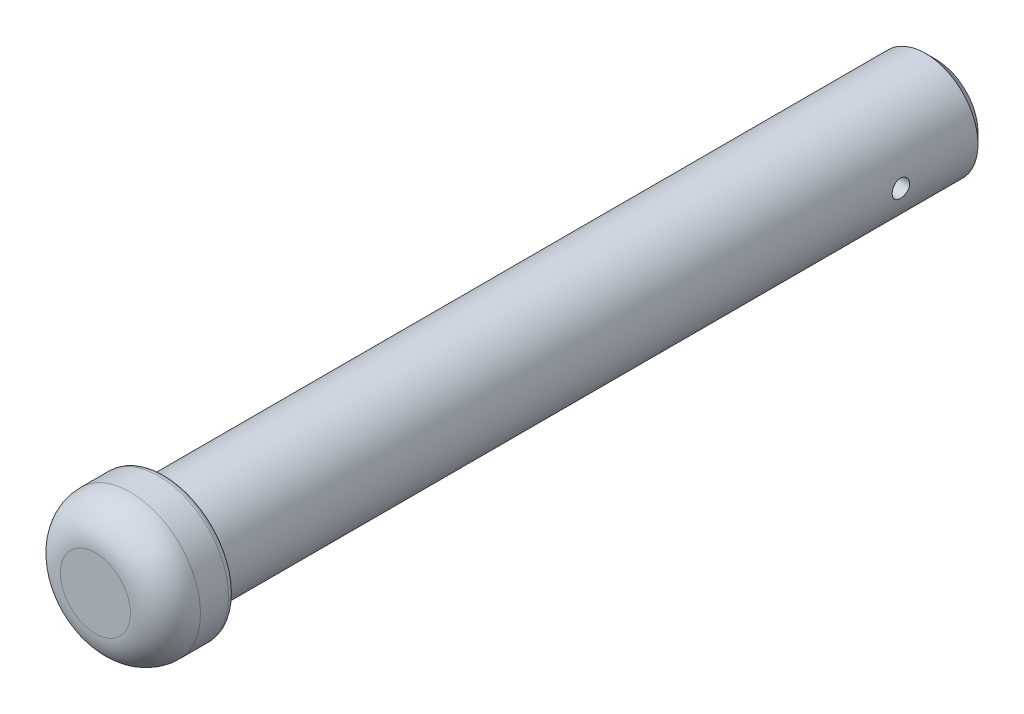
SolidWorks part; units mm, degrees
material "1.1191 (C45E)"
ref_plane "Front Plane" through (0, 0, 0) normal (0, 0, 1) x (1, 0, 0)
ref_plane "Top Plane" through (0, 0, 0) normal (0, 1, 0) x (1, 0, 0)
ref_plane "Right Plane" through (0, 0, 0) normal (1, 0, 0) x (0, 0, -1)
sketch "Sketch1" plane through (0, 0, 0) normal (0, 0, 1) x (1, 0, 0)
  circle A0 centre (0, 0) radius 15
  dimension "D1" = 30
extrude "Boss-Extrude1" add sketch "Sketch1" along normal blind 220
sketch "Sketch2" plane through (0, 0, 220) normal (0, 0, 1) x (1, 0, 0)
  circle A0 centre (0, 0) radius 20
  dimension "D1" = 40
extrude "Boss-Extrude2" add sketch "Sketch2" along normal blind 20
fillet "Fillet1" radius 10 1 edges at (20, 0, 240)
fillet "Fillet2" radius 2 2 edges at (15, 0, 220) (20, 0, 220)
chamfer "Chamfer1" distance 3 angle 45 1 edges at (15, 0, 0)
sketch "Sketch4" plane through (0, 0, 0) normal (1, 0, 0) x (0, 0, -1)
  line L0 (-3, 15) -> (-3, -15) construction
  line L1 (-218, 0) -> (-3, 0) construction
  circle A0 centre (-25, 0) radius 2.5
  dimension "D1" = 2.5
  dimension "D2" = 22
extrude "Cut-Extrude1" cut sketch "Sketch4" against normal through all both and the other way through all
sketch "Sketch5" plane through (0, 0, 0) normal (1, 0, 0) x (0, 0, -1)
  point P0 (-25, 0)
ref_plane "Plane1" through (0, 0, 25) normal (0, 0, -1) x (-1, 0, 0)
